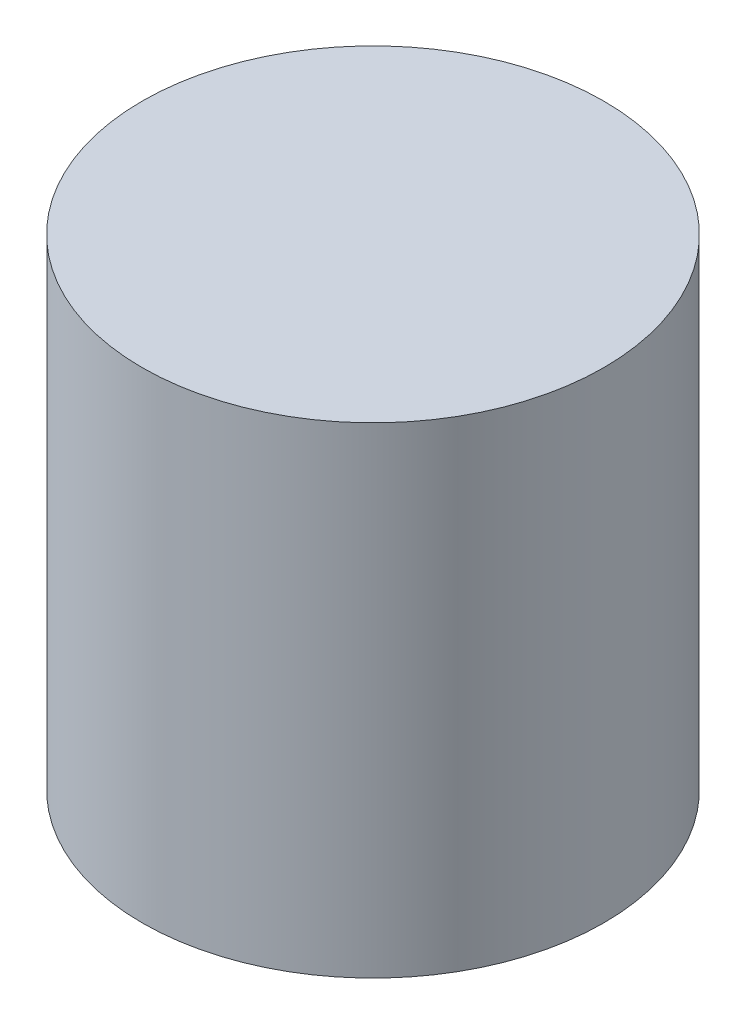
SolidWorks part; units mm, degrees
ref_plane "Front Plane" through (0, 0, 0) normal (0, 0, 1) x (1, 0, 0)
ref_plane "Top Plane" through (0, 0, 0) normal (0, 1, 0) x (1, 0, 0)
ref_plane "Right Plane" through (0, 0, 0) normal (1, 0, 0) x (0, 0, -1)
sketch "Sketch1" plane through (0, 0, 0) normal (0, 1, 0) x (1, 0, 0)
  circle A0 centre (0, 0) radius 4.8
extrude "Boss-Extrude1" add sketch "Sketch1" along normal blind 10
